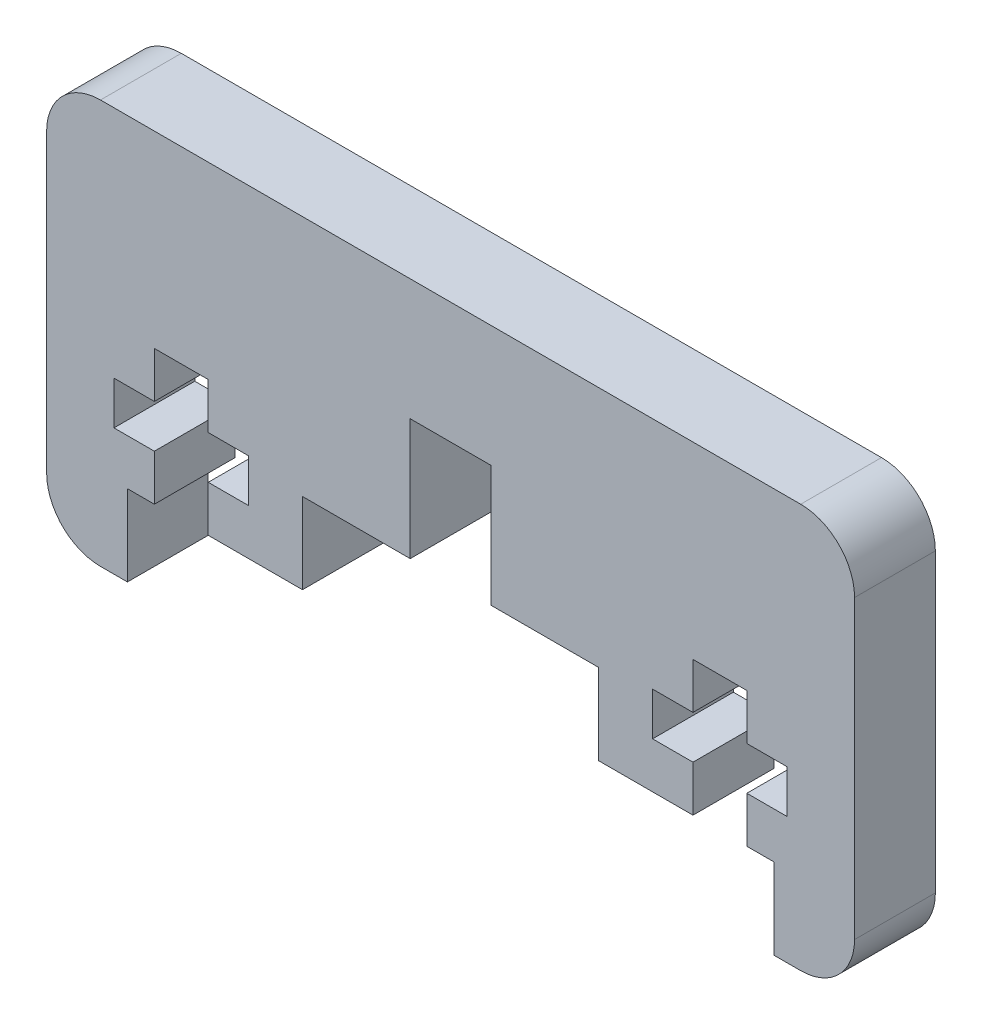
SolidWorks part; units mm, degrees
ref_plane "Plan de face" through (0, 0, 0) normal (0, 0, 1) x (1, 0, 0)
ref_plane "Plan de dessus" through (0, 0, 0) normal (0, 1, 0) x (1, 0, 0)
ref_plane "Plan de droite" through (0, 0, 0) normal (1, 0, 0) x (0, 0, -1)
sketch "Esquisse1" plane through (0, 0, 0) normal (0, 0, 1) x (1, 0, 0)
  line L0 (-75, -27.5) -> (75, -27.5) construction
  line L1 (-65, 37.5) -> (65, 37.5)
  line L2 (-75, 27.5) -> (-75, -27.5)
  line L3 (-65, -37.5) -> (65, -37.5)
  line L4 (75, 27.5) -> (75, -27.5)
  line L5 (-75, 37.5) -> (75, -37.5) construction
  line L6 (-75, -37.5) -> (75, 37.5) construction
  line L7 (0, 37.5) -> (0, -37.5) construction
  line L8 (60, -37.5) -> (0, -37.5)
  line L9 (60, -37.5) -> (60, -22.5)
  line L10 (0, -37.5) -> (0, -22.5) construction
  line L11 (60, -22.5) -> (-60, -22.5)
  line L12 (55, -22.5) -> (45, -22.5)
  line L13 (55, -22.5) -> (55, -13.9737)
  line L14 (45, -22.5) -> (45, -13.9737)
  line L15 (55, 2.5527) -> (45, 2.5527)
  line L16 (45, 2.5527) -> (55, -22.5) construction
  line L17 (55, 2.5527) -> (45, -22.5) construction
  line L18 (-55, 2.5527) -> (-45, 2.5527)
  line L19 (37.5, -13.9737) -> (45, -13.9737)
  line L20 (37.5, -13.9737) -> (37.5, -5.9737)
  line L21 (37.5, -5.9737) -> (45, -5.9737)
  line L22 (62.5, -13.9737) -> (62.5, -5.9737)
  line L23 (37.5, -13.9737) -> (62.5, -5.9737) construction
  line L24 (37.5, -5.9737) -> (62.5, -13.9737) construction
  line L25 (-37.5, -13.9737) -> (-37.5, -5.9737)
  line L26 (-62.5, -13.9737) -> (-62.5, -5.9737)
  line L27 (-37.5, -5.9737) -> (-45, -5.9737)
  line L28 (-37.5, -13.9737) -> (-45, -13.9737)
  line L29 (-45, -22.5) -> (-45, -13.9737)
  line L30 (-55, -22.5) -> (-55, -13.9737)
  line L31 (-60, -37.5) -> (-60, -22.5)
  line L32 (55, -5.9737) -> (55, 2.5527)
  line L33 (45, -5.9737) -> (45, 2.5527)
  line L34 (-45, -5.9737) -> (-45, 2.5527)
  line L35 (-55, -5.9737) -> (-55, 2.5527)
  line L36 (-55, -5.9737) -> (-62.5, -5.9737)
  line L37 (-55, -13.9737) -> (-62.5, -13.9737)
  line L38 (55, -5.9737) -> (62.5, -5.9737)
  line L39 (55, -13.9737) -> (62.5, -13.9737)
  line L40 (7.5, -22.5) -> (-7.5, -22.5)
  line L41 (7.5, -22.5) -> (7.5, 15)
  line L42 (-7.5, -22.5) -> (-7.5, 15)
  line L43 (7.5, 15) -> (-7.5, 15)
  line L44 (-27.5, -22.5) -> (-27.5, -7.5)
  line L45 (-27.5, -7.5) -> (27.5, -7.5)
  line L46 (27.5, -7.5) -> (27.5, -22.5)
  arc A0 (75, -27.5) -> (65, -37.5) centre (65, -27.5) cw
  arc A1 (-65, -37.5) -> (-75, -27.5) centre (-65, -27.5) cw
  arc A2 (-75, 27.5) -> (-65, 37.5) centre (-65, 27.5) cw
  arc A3 (75, 27.5) -> (65, 37.5) centre (65, 27.5) ccw
  point P0 (0, 0)
  point P20 (50, -9.9737)
  dimension "D3" = 10
  dimension "D1" = 150
  dimension "D2" = 75
  dimension "D4" = 15
  dimension "D5" = 15
  dimension "D6" = 10
  dimension "D7" = 5
  dimension "D8" = 8
  dimension "D9" = 25
  dimension "D10" = 7.5
  dimension "D11" = 15
  dimension "D12" = 22.5
extrude "Boss.-Extru.1" add sketch "Esquisse1" along normal blind 15 contours L4 A3 L1 A2 L2 A1 L3 L31 L11 L30 L37 L26 L36 L35 L18 L34 L27 L25 L28 L29 L14 L19 L20 L21 L33 L15 L32 L38 L22 L39 L13 L9 A0
